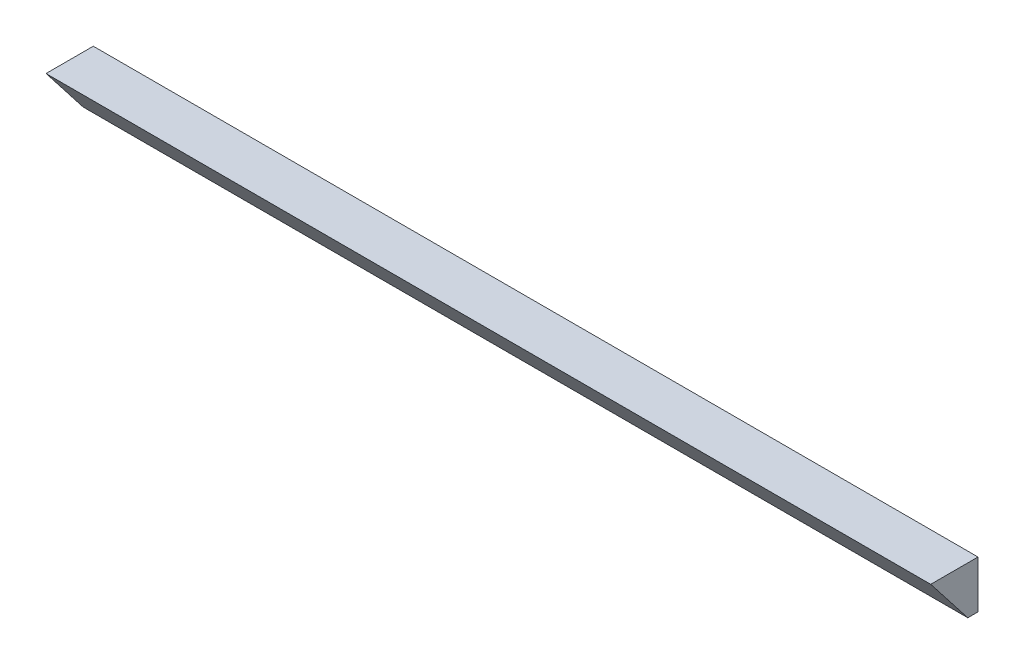
SolidWorks part; units mm, degrees
ref_plane "Plano frontal" through (0, 0, 0) normal (0, 0, 1) x (1, 0, 0)
ref_plane "Plano superior" through (0, 0, 0) normal (0, 1, 0) x (1, 0, 0)
ref_plane "Plano direito" through (0, 0, 0) normal (1, 0, 0) x (0, 0, -1)
sketch "Esboço61" plane through (55.1891, 0, 0) normal (-1, 0, 0) x (0, 0, 1)
  line L0 (38, -40.3645) -> (38, -35.3645)
  line L1 (38, -35.3645) -> (42.9711, -35.3645)
  line L2 (42.9711, -35.3645) -> (39.0703, -40.3645)
  line L3 (38, -40.3645) -> (39.0703, -40.3645)
  arc A0 (17.5, -49.5145) -> (17.5, 10.4855) centre (17.5, -19.5145) ccw construction
extrude "Ressalto-extrusão16" add sketch "Esboço61" along normal blind 93 separate body
